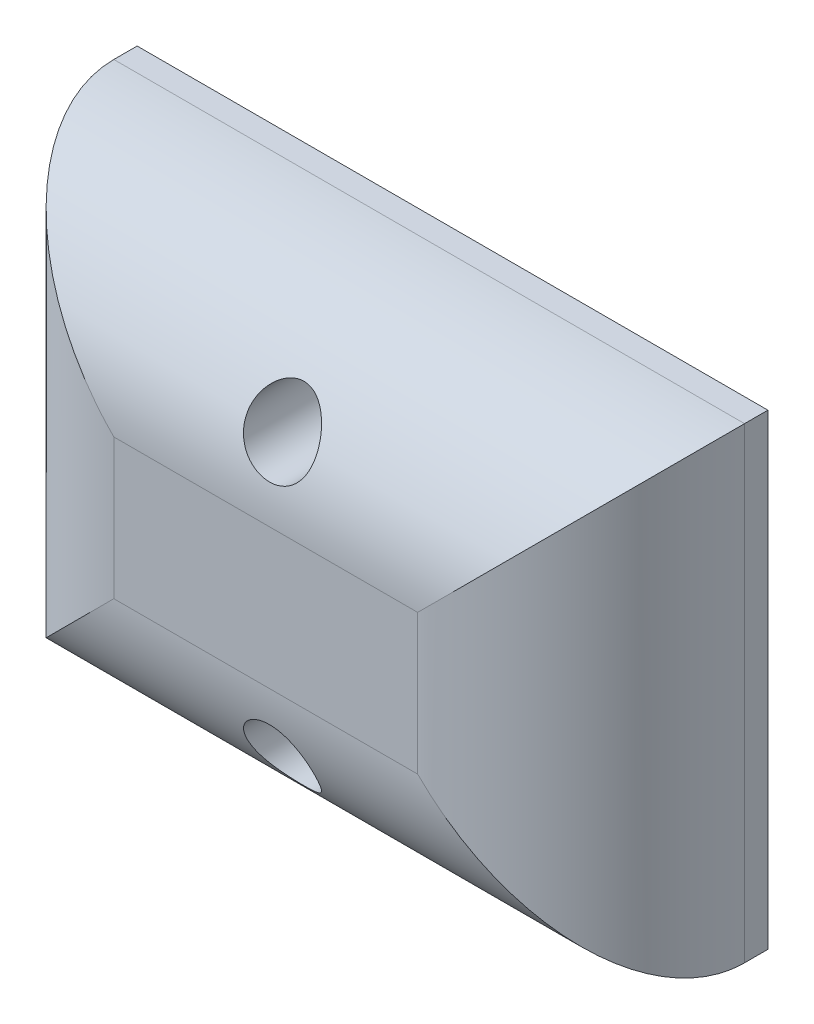
SolidWorks part; units mm, degrees
ref_plane "Ebene vorne" through (0, 0, 0) normal (0, 0, 1) x (1, 0, 0)
ref_plane "Ebene oben" through (0, 0, 0) normal (0, 1, 0) x (1, 0, 0)
ref_plane "Ebene rechts" through (0, 0, 0) normal (1, 0, 0) x (0, 0, -1)
sketch "Skizze1" plane through (0, 0, 0) normal (0, 0, 1) x (1, 0, 0)
  line L1 (67.5347, -50) -> (-67.5347, -50)
  line L2 (67.5347, -50) -> (67.5347, 50)
  line L3 (67.5347, 50) -> (-67.5347, 50)
  line L4 (-67.5347, -50) -> (-67.5347, 50)
  line L5 (67.5347, -50) -> (-67.5347, 50) construction
  line L6 (67.5347, 50) -> (-67.5347, -50) construction
  point P0 (0, 0)
  dimension "D1" = 100
  dimension "D2" = 135.0694
extrude "Aufsatz-Linear austragen1" add sketch "Skizze1" along normal blind 40 contours L3 L4 L1 L2
sketch "Skizze2" plane through (67.5347, 0, 0) normal (1, 0, 0) x (0, 0, -1)
  line L0 (-40, -50) -> (-40, 50) construction
  line L1 (-40, 50) -> (0, 50) construction
  line L3 (-5, 50) -> (42.4219, 50)
  line L4 (42.4219, 50) -> (-56.728, 80.8298)
  line L5 (-56.728, 80.8298) -> (-40, -11.6554)
  line L6 (-40, -11.6554) -> (-40, 15)
  arc A0 (-5, 50) -> (-40, 15) centre (-5, 15) ccw
  dimension "D1" = 35
extrude "Schnitt-Linear austragen1" cut sketch "Skizze2" against normal through all
mirror "Spiegeln1" about plane through (0, 0, 0) normal (0, 1, 0) of "Schnitt-Linear austragen1"
sketch "Skizze5" plane through (0, 50, 0) normal (0, 1, 0) x (1, 0, 0)
  line L0 (-67.5347, -5) -> (-67.5347, -19.8724)
  line L1 (-67.5347, -19.8724) -> (-98.3646, -61.728)
  line L2 (-98.3646, -61.728) -> (-5.8793, -40)
  line L3 (-5.8793, -40) -> (-32.5347, -40)
  line L4 (-67.5347, -5) -> (-67.5347, 0) construction
  line L5 (-67.5347, -40) -> (67.5347, -40) construction
  arc A0 (-67.5347, -5) -> (-32.5347, -40) centre (-32.5347, -5) ccw
extrude "Schnitt-Linear austragen2" cut sketch "Skizze5" against normal through all
mirror "Spiegeln2" about plane through (0, 0, 0) normal (1, 0, 0) of "Schnitt-Linear austragen2"
sketch "Skizze13" plane through (0, 0, 40) normal (0, 0, 1) x (1, 0, 0)
  line L0 (32.5347, -15) -> (32.5347, 15) construction
  line L1 (-32.5347, -15) -> (-32.5347, 15) construction
  line L2 (-67.5347, -50) -> (67.5347, -50) construction
  circle A0 centre (0, -30) radius 32.5347
  dimension "D1" = 20
hole_wizard "Stirnsenkung für M8 Senkschraube (Kopf Button)3" positions "Skizze15" profile "Skizze16" counterbore size "M8" standard "ANSI Metrisch" end condition through all
sketch "Skizze15" plane through (0, 0, 40) normal (0, 0, 1) x (1, 0, 0)
  point P0 (0, -30)
sketch "Skizze16" plane through (0, -30, 40) normal (1, 0, 0) x (0, -1, 0)
  line L0 (0, 0) -> (0, 40)
  line L1 (0, 40) -> (4.5, 40)
  line L3 (4.5, 40) -> (4.5, 35)
  line L4 (4.5, 35) -> (7.5, 35)
  line L5 (7.5, 35) -> (7.5, 0)
  line L7 (7.5, 0) -> (0, 0)
  line L11 (0, -6.35) -> (0, 107.95) construction
  dimension "Bohrerdurchmesser" = 9
  dimension "Bohrungstiefe" = 40
  dimension "Senkdurchmesser2" = 15
  dimension "Senktiefe2" = 35
mirror "Spiegeln5" about plane through (0, 0, 0) normal (0, 1, 0) of "Stirnsenkung für M8 Senkschraube (Kopf Button)3"
